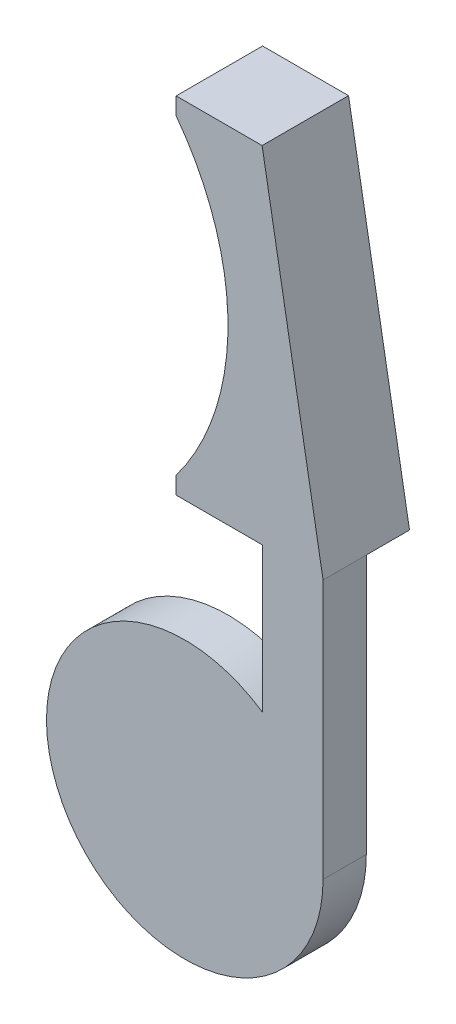
SolidWorks part; units mm, degrees
ref_plane "Front Plane" through (0, 0, 0) normal (0, 0, 1) x (1, 0, 0)
ref_plane "Top Plane" through (0, 0, 0) normal (0, 1, 0) x (1, 0, 0)
ref_plane "Right Plane" through (0, 0, 0) normal (1, 0, 0) x (0, 0, -1)
sketch "Sketch1" plane through (0, 0, 0) normal (0, 0, 1) x (1, 0, 0)
  circle A0 centre (0, 0) radius 20.32
  dimension "D1" = 40.64
extrude "Boss-Extrude1" add sketch "Sketch1" along normal blind 6.35
sketch "Sketch2" plane through (0, 0, 0) normal (0, 0, -1) x (-1, 0, 0)
  circle A0 centre (0, 0) radius 4.445
  circle A1 centre (0, 0) radius 3.175
  dimension "D1" = 8.89
  dimension "D2" = 6.35
extrude "Boss-Extrude2" add sketch "Sketch2" along normal blind 2.54
sketch "Sketch4" plane through (0, 0, 6.35) normal (0, 0, 1) x (1, 0, 0)
  line L1 (20.32, 0) -> (11.43, 0)
  line L2 (20.32, 0) -> (20.32, 38.1)
  line L3 (20.32, 38.1) -> (11.43, 38.1)
  line L4 (11.43, 0) -> (11.43, 38.1)
  circle A0 centre (0, 0) radius 20.32 construction
  point P6 (20.32, 0)
  point P8 (0, 0)
  dimension "D1" = 8.89
  dimension "D2" = 38.1
extrude "Boss-Extrude3" add sketch "Sketch4" against normal up to surface (6.35 mm away) up to face at (4.445, 0, 0)
sketch "Sketch5" plane through (0, 0, 6.35) normal (0, 0, 1) x (1, 0, 0)
  line L0 (20.32, 38.1) -> (-1.27, 38.1)
  line L1 (-1.27, 38.1) -> (-1.27, 40.64)
  line L2 (-1.27, 86.36) -> (-1.27, 88.9)
  line L3 (-1.27, 88.9) -> (11.3626, 88.9)
  line L4 (11.3626, 88.9) -> (20.32, 38.1)
  line L5 (11.43, 38.1) -> (11.43, 16.8005) construction
  arc A0 (-1.27, 40.64) -> (-1.27, 86.36) centre (-31.75, 63.5) ccw
  point P10 (20.2757, 38.3514)
  dimension "D3" = 38.1
  dimension "D1" = 50.8
  dimension "D2" = 2.54
  dimension "D4" = 80
  dimension "D5" = 12.7
extrude "Boss-Extrude4" add sketch "Sketch5" against normal blind 12.7
